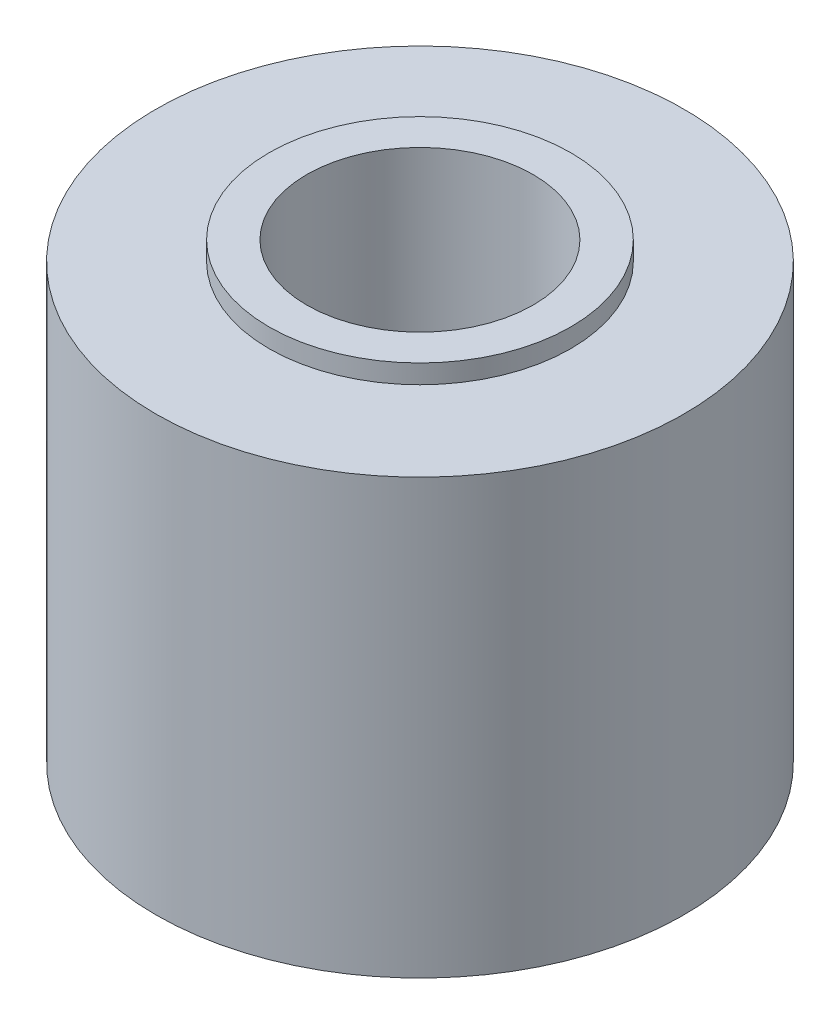
SolidWorks part; units mm, degrees
material "Nylon 101"
ref_plane "Front Plane" through (0, 0, 0) normal (0, 0, 1) x (1, 0, 0)
ref_plane "Top Plane" through (0, 0, 0) normal (0, 1, 0) x (1, 0, 0)
ref_plane "Right Plane" through (0, 0, 0) normal (1, 0, 0) x (0, 0, -1)
sketch "Sketch1" plane through (0, 0, 0) normal (0, 1, 0) x (1, 0, 0)
  circle A0 centre (0, 0) radius 7
  circle A1 centre (0, 0) radius 3
  dimension "D1" = 14
  dimension "D2" = 6
extrude "Boss-Extrude1" add sketch "Sketch1" along normal blind 14
sketch "Sketch2" plane through (0, 0, 0) normal (0, 0, 1) x (1, 0, 0)
  line L0 (-7, 0) -> (7, 0) construction
  line L1 (4, 0) -> (7, 0)
  line L2 (4, 0) -> (4, 2)
  line L3 (4, 2) -> (7, 2)
  line L4 (7, 0) -> (7, 2)
  line L5 (7, 0) -> (7, 14) construction
  line L6 (7, 14) -> (-7, 14) construction
  line L7 (7, 13.5) -> (4, 13.5)
  line L8 (7, 13.5) -> (7, 14)
  line L9 (7, 14) -> (4, 14)
  line L10 (4, 13.5) -> (4, 14)
  dimension "D1" = 2
  dimension "D2" = 0.5
  dimension "D3" = 3
ref_axis "Axis1" through (0, 14, 0) along (0, -1, 0)
revolve "Cut-Revolve1" cut sketch "Sketch2" angle 360 about axis through (0, 14, 0) along (0, -1, 0)
